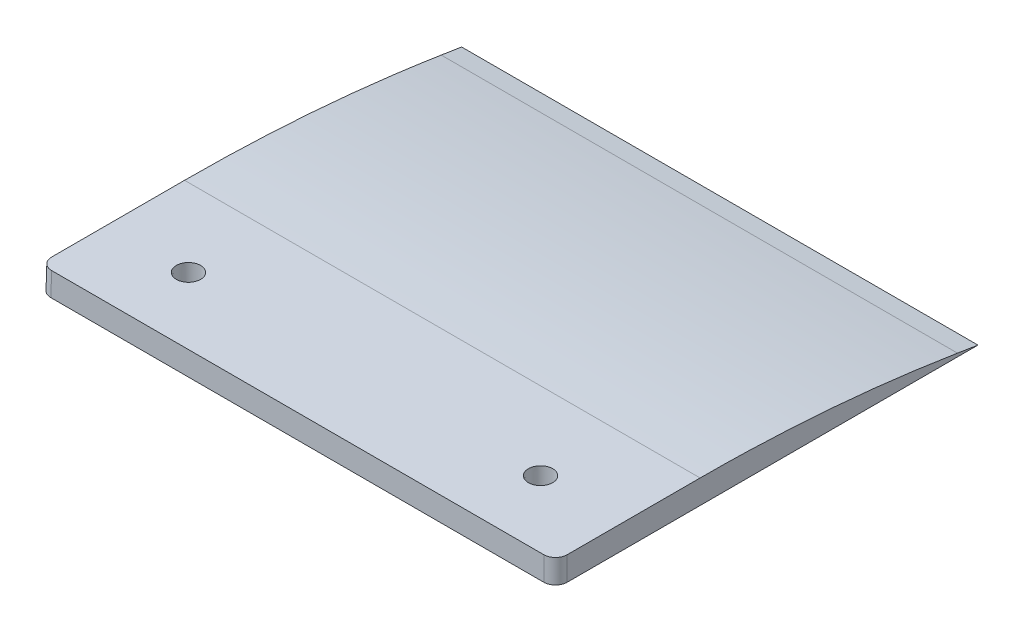
SolidWorks part; units mm, degrees
ref_plane "前视基准面" through (0, 0, 0) normal (0, 0, 1) x (1, 0, 0)
ref_plane "上视基准面" through (0, 0, 0) normal (0, 1, 0) x (1, 0, 0)
ref_plane "右视基准面" through (0, 0, 0) normal (1, 0, 0) x (0, 0, -1)
sketch "草图1" plane through (0, 0, 0) normal (0, 1, 0) x (1, 0, 0)
  line L0 (-75, -61.3636) -> (75, -61.3636) construction
  line L1 (-110, -90) -> (110, -90)
  line L2 (-110, -90) -> (-110, 90)
  line L3 (-110, 90) -> (110, 90)
  line L4 (110, -90) -> (110, 90)
  line L5 (-110, -90) -> (110, 90) construction
  line L6 (-110, 90) -> (110, -90) construction
  circle A0 centre (-75, -61.3636) radius 5
  circle A1 centre (75, -61.3636) radius 5
  point P0 (0, 0)
  dimension "D3" = 10
  dimension "D4" = 10
  dimension "D1" = 220
  dimension "D2" = 180
  dimension "D5" = 150
extrude "凸台-拉伸1" add sketch "草图1" along normal blind 10 draft 1
fillet "圆角1" radius 5 2 edges at (109.9127, 5, 89.9127) (-109.9127, 5, 89.9127)
chamfer "倒角1" distance 10 angle 80 1 edges at (0, 10, -89.8254)
fillet "圆角2" radius 700 1 edges at (0, 10, -26.8721)
